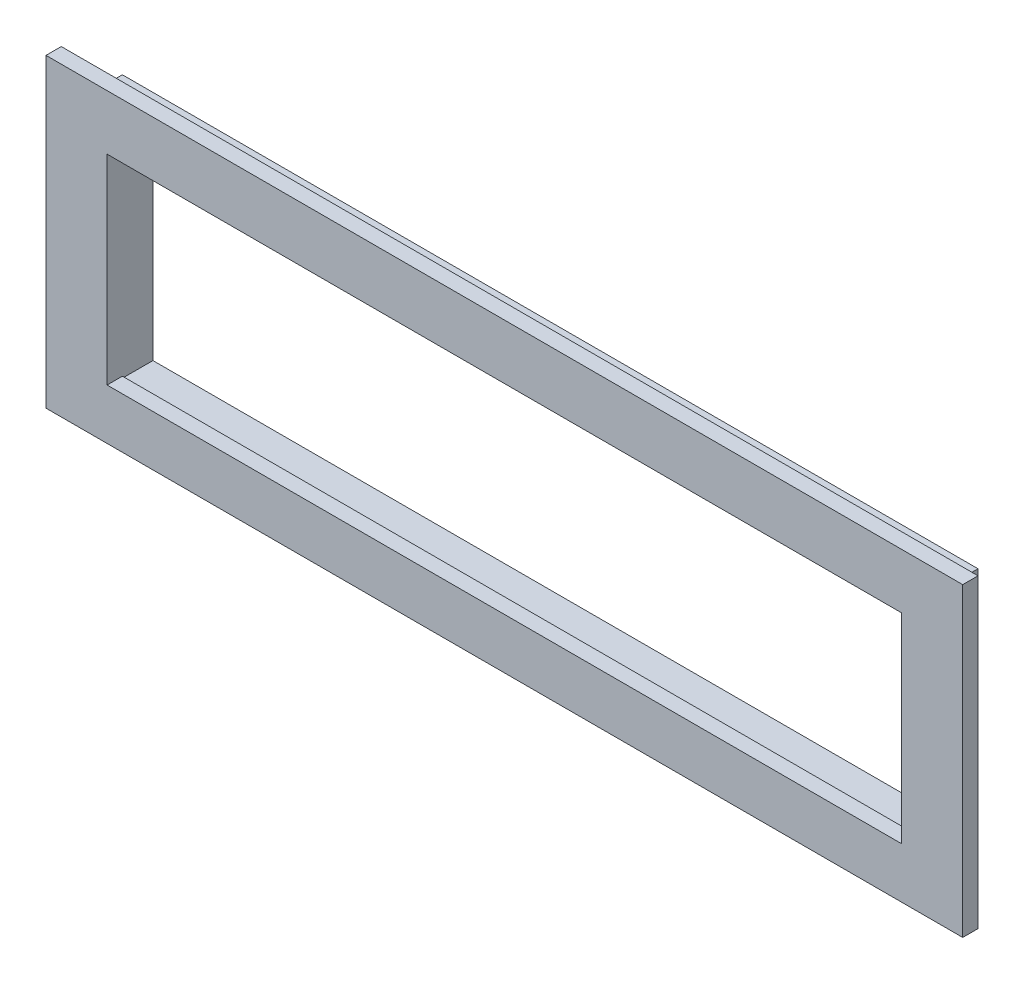
SolidWorks part; units mm, degrees
ref_plane "Спереди" through (0, 0, 0) normal (0, 0, 1) x (1, 0, 0)
ref_plane "Сверху" through (0, 0, 0) normal (0, 1, 0) x (1, 0, 0)
ref_plane "Справа" through (0, 0, 0) normal (1, 0, 0) x (0, 0, -1)
sketch "Эскиз1" plane through (0, 0, 0) normal (0, 0, 1) x (1, 0, 0)
  line L1 (-35.5884, -20.389) -> (-7.5884, -20.389) construction
  line L2 (-35.5884, -24.689) -> (-7.5884, -24.689)
  line L3 (-35.5884, -24.689) -> (-35.5884, -16.089)
  line L4 (-35.5884, -16.089) -> (-7.5884, -16.089)
  line L5 (-7.5884, -24.689) -> (-7.5884, -16.089)
  line L7 (-8.5884, -17.089) -> (-34.5884, -17.089)
  line L8 (-8.5884, -17.089) -> (-8.5884, -23.689)
  line L9 (-8.5884, -23.689) -> (-34.5884, -23.689)
  line L10 (-34.5884, -17.089) -> (-34.5884, -23.689)
  line L11 (-8.5884, -17.089) -> (-34.5884, -23.689) construction
  line L12 (-8.5884, -23.689) -> (-34.5884, -17.089) construction
  point P6 (-21.5884, -20.389)
extrude "Бобышка-Вытянуть1" add sketch "Эскиз1" against normal blind 1
sketch "Эскиз2" plane through (0, 0, 0) normal (0, 0, 1) x (1, 0, 0)
  line L0 (-8.5884, -23.689) -> (-8.5884, -17.089) construction
  line L1 (-8.5884, -23.632) -> (-34.5884, -23.632)
  line L2 (-8.5884, -23.632) -> (-8.5884, -17.089)
  line L3 (-8.5884, -17.089) -> (-34.5884, -17.089)
  line L4 (-34.5884, -23.632) -> (-34.5884, -17.089)
  line L6 (-6.5884, -25.289) -> (-36.5884, -25.289)
  line L7 (-6.5884, -25.289) -> (-6.5884, -15.289)
  line L8 (-6.5884, -15.289) -> (-36.5884, -15.289)
  line L9 (-36.5884, -25.289) -> (-36.5884, -15.289)
extrude "Бобышка-Вытянуть2" add sketch "Эскиз2" along normal blind 0.5
sketch "Эскиз3" plane through (-34.5884, 0, 0) normal (1, 0, 0) x (0, 0, -1)
  line L0 (-7.6, -0.289) -> (-7.6, -25.289) construction
  line L1 (-7.6, -25.289) -> (-0.5, -25.289) construction
  line L2 (-5.6, -0.289) -> (-5.6, -7.1072) construction
  line L3 (-5.6, 0.144) -> (-5.6, -0.722) construction
  line L4 (-0.5, -15.289) -> (-0.5, -17.089)
  line L6 (-0.5, -25.289) -> (-0.5, -23.689) construction
  line L7 (-0.5, -25.289) -> (-5.6, -25.289)
  line L9 (-5.6, -25.289) -> (-5.6, -11.6019)
  line L10 (-4.1153, -9.489) -> (-0.5, -15.289)
  line L12 (-5.6, -11.6019) -> (-5.6, -25.289) construction
  line L15 (-4.4486, -10.8447) -> (-1.3486, -15.818)
  line L16 (-0.5, -17.089) -> (-1.3486, -15.818)
  line L18 (-4.6, -9.489) -> (-4.1153, -9.489)
  line L19 (-4.6, -9.489) -> (-4.6, -10.3157)
  line L20 (-0.5, -23.689) -> (-4.6, -23.689)
  line L21 (-0.5, -23.689) -> (-0.5, -25.289)
  line L23 (-4.6, -12.1019) -> (-4.6, -23.689)
  line L24 (-5.1, -11.6019) -> (-5.6, -11.6019)
  arc A0 (-5.1, -11.6019) -> (-4.6, -12.1019) centre (-5.1, -12.1019) cw
  arc A1 (-4.4486, -10.8447) -> (-4.6, -10.3157) centre (-3.6, -10.3157) cw
  dimension "D1" = 0.5
  dimension "D2" = 1
sketch "Эскиз4" plane through (-6.5884, 0, 0) normal (1, 0, 0) x (0, 0, -1)
  line L0 (-7.6, -0.289) -> (-7.6, -25.289) construction
  line L1 (-7.6, -25.289) -> (-0.5, -25.289) construction
  line L3 (-0.5, -15.289) -> (-0.5, -25.289)
  line L5 (-0.5, -25.289) -> (-0.5, -20.289) construction
  line L6 (-0.5, -25.289) -> (-4.6, -25.289)
  line L7 (-5.6, -24.289) -> (-5.6, -7.8061)
  line L8 (-0.5, -15.289) -> (-5.2303, -7.7003)
  line L10 (-5.6, -7.1072) -> (-5.6, -25.289) construction
  arc A0 (-4.6, -25.289) -> (-5.6, -24.289) centre (-4.6, -24.289) cw
  arc A2 (-5.2303, -7.7003) -> (-5.6, -7.8061) centre (-5.4, -7.8061) ccw
  dimension "D1" = 1
  dimension "D2" = 0.2
